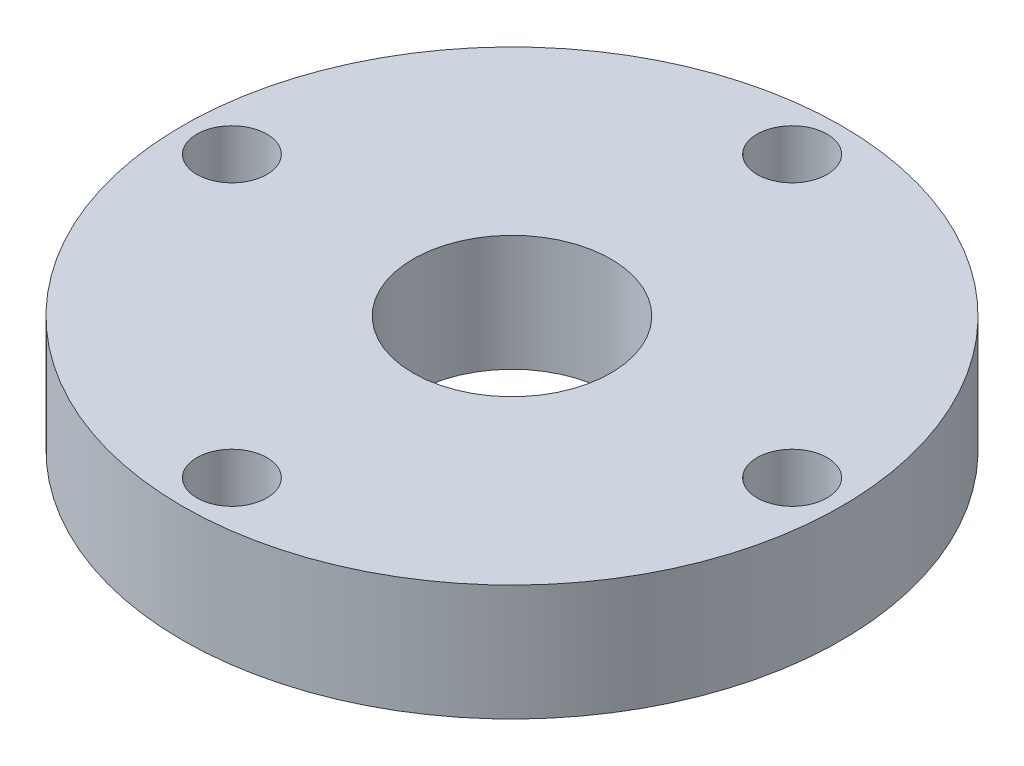
SolidWorks part; units mm, degrees
ref_plane "Front Plane" through (0, 0, 0) normal (1, 0, 0) x (0, 1, 0)
ref_plane "Top Plane" through (0, 0, 0) normal (0, 0, 1) x (0, 1, 0)
ref_plane "Right Plane" through (0, 0, 0) normal (0, 1, 0) x (-1, 0, 0)
sketch "Sketch1" plane through (0, 0, 0) normal (0, 0, 1) x (0, 1, 0)
  line L0 (-11.176, 0) -> (-11.176, 63.5)
  line L1 (-11.176, 63.5) -> (11.176, 63.5)
  line L2 (11.176, 63.5) -> (11.176, 0)
  line L3 (11.176, 0) -> (-11.176, 0)
  line L4 (-36.576, 0) -> (36.576, 0) construction
revolve "Revolve1" add sketch "Sketch1" angle 360 about L4
sketch "Sketch2" plane through (0, 0, 0) normal (0, 1, 0) x (-1, 0, 0)
  circle A0 centre (0, 0) radius 19.05
extrude "Cut-Extrude2" cut sketch "Sketch2" against normal through all from offset 11.176
sketch "Sketch3" plane through (0, 0, 0) normal (0, 1, 0) x (-1, 0, 0)
  circle A0 centre (53.975, 0) radius 4.3688
extrude "Cut-Extrude4" cut sketch "Sketch3" against normal blind 127 from offset 11.176
sketch "Sketch4" plane through (0, 0, 0) normal (0, 1, 0) x (-1, 0, 0)
  circle A0 centre (53.975, 0) radius 6.7437
extrude "Cut-Extrude6" cut sketch "Sketch4" against normal blind 9.652 from offset 11.176
sketch "Sketch5" plane through (0, 0, 0) normal (0, 1, 0) x (-1, 0, 0)
  circle A0 centre (0, 53.975) radius 4.3688
  circle A1 centre (-53.975, 0) radius 4.3688
  circle A2 centre (0, -53.975) radius 4.3688
extrude "Cut-Extrude8" cut sketch "Sketch5" against normal blind 127 from offset 11.176
sketch "Sketch6" plane through (0, 0, 0) normal (0, 1, 0) x (-1, 0, 0)
  circle A0 centre (0, 53.975) radius 6.7437
  circle A1 centre (-53.975, 0) radius 6.7437
  circle A2 centre (0, -53.975) radius 6.7437
extrude "Cut-Extrude10" cut sketch "Sketch6" against normal blind 9.652 from offset 11.176
